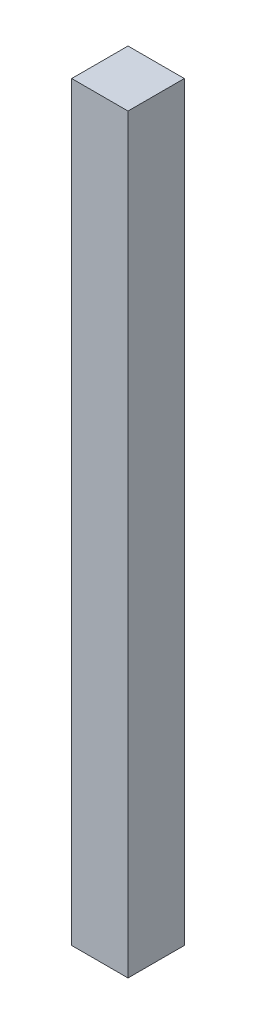
SolidWorks part; units mm, degrees
ref_plane "Front Plane" through (0, 0, 0) normal (0, 0, 1) x (1, 0, 0)
ref_plane "Top Plane" through (0, 0, 0) normal (0, 1, 0) x (1, 0, 0)
ref_plane "Right Plane" through (0, 0, 0) normal (1, 0, 0) x (0, 0, -1)
sketch "Sketch1" plane through (0, 0, 0) normal (0, 1, 0) x (1, 0, 0)
  line L1 (-4.7625, -4.7625) -> (4.7625, -4.7625)
  line L2 (-4.7625, -4.7625) -> (-4.7625, 4.7625)
  line L3 (-4.7625, 4.7625) -> (4.7625, 4.7625)
  line L4 (4.7625, -4.7625) -> (4.7625, 4.7625)
  line L5 (-4.7625, -4.7625) -> (4.7625, 4.7625) construction
  line L6 (-4.7625, 4.7625) -> (4.7625, -4.7625) construction
  point P0 (0, 0)
  dimension "D1" = 9.525
  dimension "D2" = 9.525
extrude "Boss-Extrude1" add sketch "Sketch1" along normal blind 127
